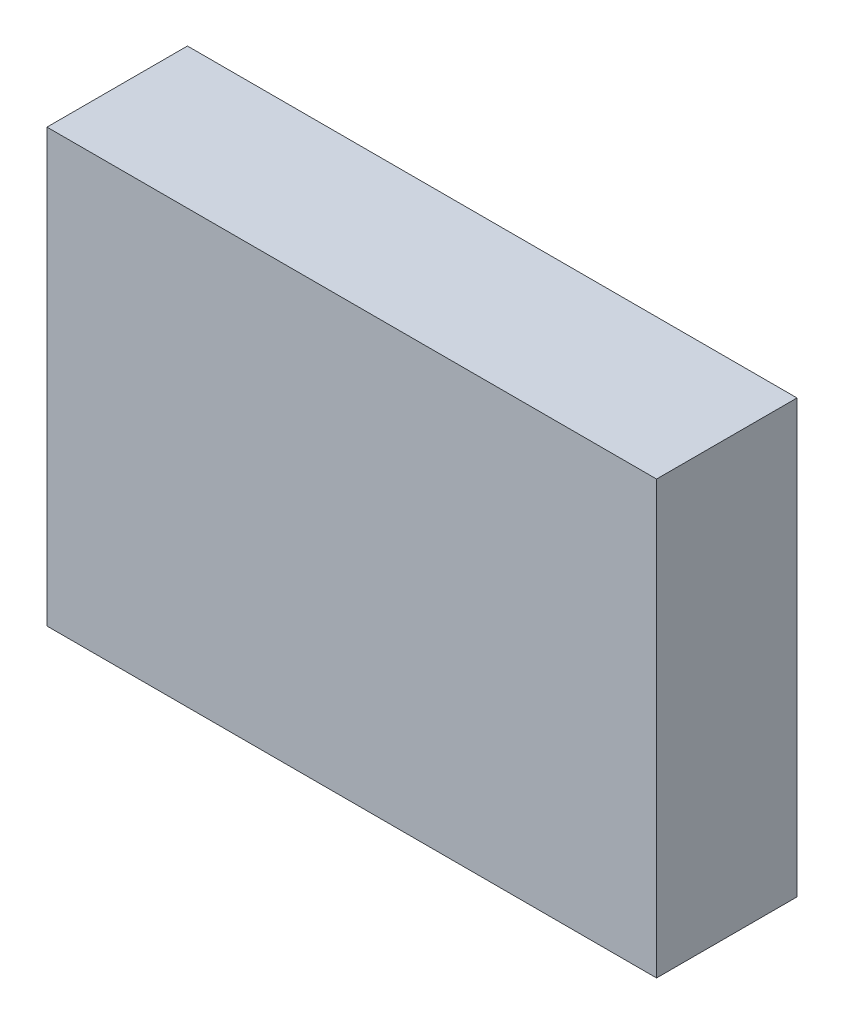
SolidWorks part; units mm, degrees
ref_plane "Front Plane" through (0, 0, 0) normal (0, 0, 1) x (1, 0, 0)
ref_plane "Top Plane" through (0, 0, 0) normal (0, 1, 0) x (1, 0, 0)
ref_plane "Right Plane" through (0, 0, 0) normal (1, 0, 0) x (0, 0, -1)
sketch "Sketch1" plane through (0, 0, 0) normal (0, 0, 1) x (1, 0, 0)
  line L1 (-55.1185, -39.0725) -> (55.1185, -39.0725)
  line L2 (-55.1185, -39.0725) -> (-55.1185, 39.0725)
  line L3 (-55.1185, 39.0725) -> (55.1185, 39.0725)
  line L4 (55.1185, -39.0725) -> (55.1185, 39.0725)
  line L5 (-55.1185, -39.0725) -> (55.1185, 39.0725) construction
  line L6 (-55.1185, 39.0725) -> (55.1185, -39.0725) construction
  point P0 (0, 0)
extrude "Boss-Extrude1" add sketch "Sketch1" against normal blind 25.4
